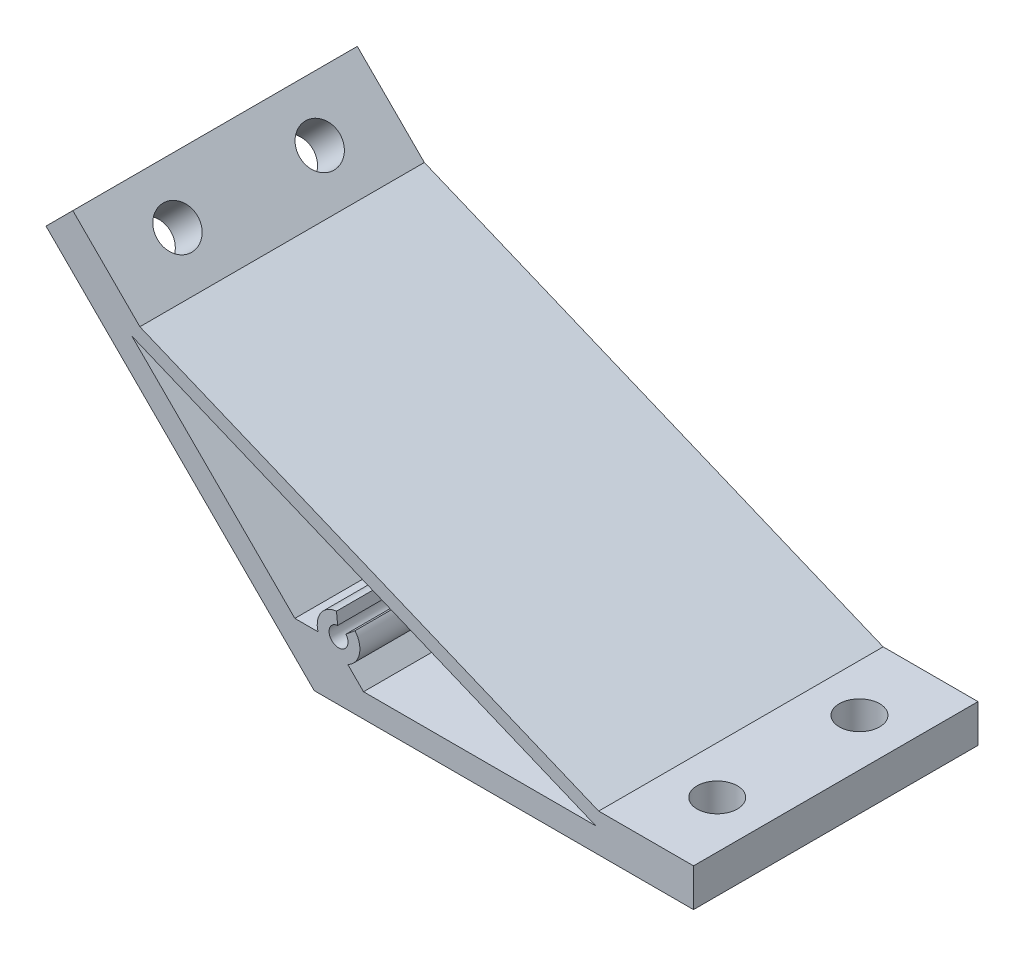
SolidWorks part; units mm, degrees
ref_plane "前视基准面" through (0, 0, 0) normal (0, 0, 1) x (1, 0, 0)
ref_plane "上视基准面" through (0, 0, 0) normal (0, 1, 0) x (1, 0, 0)
ref_plane "右视基准面" through (0, 0, 0) normal (1, 0, 0) x (0, 0, -1)
sketch "草图1" plane through (0, 0, 0) normal (0, 0, 1) x (1, 0, 0)
  line L0 (6992.6877, -1288.6549) -> (7072.6877, -1288.6549)
  line L1 (7003.0909, -1283.6549) -> (7052.0909, -1283.6549)
  line L2 (7052.6877, -1280.6549) -> (7072.6877, -1280.6549)
  line L3 (7003.0909, -1283.6549) -> (7029.4034, -1283.6549)
  line L4 (7072.6877, -1288.6549) -> (7072.6877, -1280.6549)
  line L5 (6997.6265, -1274.2736) -> (6997.3838, -1271.7854)
  line L6 (6999.3656, -1274.9939) -> (7001.2967, -1273.4062)
  line L7 (6992.6877, -1288.6549) -> (6936.1191, -1232.0864)
  line L8 (6988.6024, -1277.4986) -> (6954.2187, -1243.1149)
  line L9 (6955.9181, -1240.5717) -> (6941.776, -1226.4295)
  line L10 (6936.1191, -1232.0864) -> (6941.776, -1226.4295)
  line L11 (6955.9181, -1240.5717) -> (7052.6877, -1280.6549)
  line L12 (6954.2187, -1243.1149) -> (7052.0909, -1283.6549)
  line L13 (7052.0909, -1283.6549) -> (7009.0909, -1283.6549)
  line L14 (7003.0909, -1283.6549) -> (6999.7605, -1280.3246)
  line L15 (6988.6024, -1277.4986) -> (6993.4934, -1277.4986)
  arc A0 (6997.3838, -1271.7854) -> (6993.4934, -1277.4986) centre (6997.8207, -1276.2641) ccw
  arc A1 (6999.7605, -1280.3246) -> (7001.2967, -1273.4062) centre (6997.8207, -1276.2641) ccw
  arc A2 (6997.6265, -1274.2736) -> (6999.3656, -1274.9939) centre (6997.8207, -1276.2641) ccw
extrude "凸台-拉伸1" add sketch "草图1" along normal mid plane 60 contours L11 L9 L10 L7 L0 L4 L2 A2 L5 A0 L15 L8 L12 L1 L3 L14 A1 L6
hole_wizard "Ø8.5 (8.5) 直径孔1" positions "草图3" profile "草图2" hole size "Ø8.5" standard "GB" end condition through all
sketch "草图3" plane through (2852.0164, 2852.0164, 0) normal (-0.7071, -0.7071, 0) x (0.7071, -0.7071, 0)
  line L0 (5775.7935, 0) -> (5813.1289, 0) construction
  line L1 (5775.7935, 30) -> (5775.7935, -30) construction
  point P0 (5785.7935, -15)
  point P1 (5785.7935, 15)
  dimension "D1" = 10
  dimension "D2" = 30
sketch "草图2" plane through (6943.1902, -1239.1575, -15) normal (0, 0, 1) x (0.7071, -0.7071, 0)
  line L0 (0, 0) -> (0, 100.5685)
  line L1 (0, 100.5685) -> (4.25, 100.5685)
  line L2 (4.25, 100.5685) -> (4.25, 0)
  line L5 (4.25, 0) -> (0, 0)
  line L11 (0, -6.35) -> (0, 107.95) construction
  dimension "通孔孔直径" = 8.5
  dimension "通孔孔深度" = 100.5685
hole_wizard "Ø8.5 (8.5) 直径孔2" positions "草图5" profile "草图4" hole size "Ø8.5" standard "GB" end condition through all
sketch "草图5" plane through (0, -1288.6549, 0) normal (0, -1, 0) x (1, 0, 0)
  line L0 (7072.6877, 0) -> (7027.3225, 0) construction
  line L1 (7072.6877, 30) -> (7072.6877, -30) construction
  point P0 (7062.6877, 15)
  point P1 (7062.6877, -15)
  dimension "D1" = 30
  dimension "D2" = 10
sketch "草图4" plane through (7062.6877, -1288.6549, 15) normal (1, 0, 0) x (0, 0, -1)
  line L0 (0, 0) -> (0, 62.2254)
  line L1 (0, 62.2254) -> (4.25, 62.2254)
  line L2 (4.25, 62.2254) -> (4.25, 0)
  line L5 (4.25, 0) -> (0, 0)
  line L11 (0, -6.35) -> (0, 107.95) construction
  dimension "通孔孔直径" = 8.5
  dimension "通孔孔深度" = 62.2254
